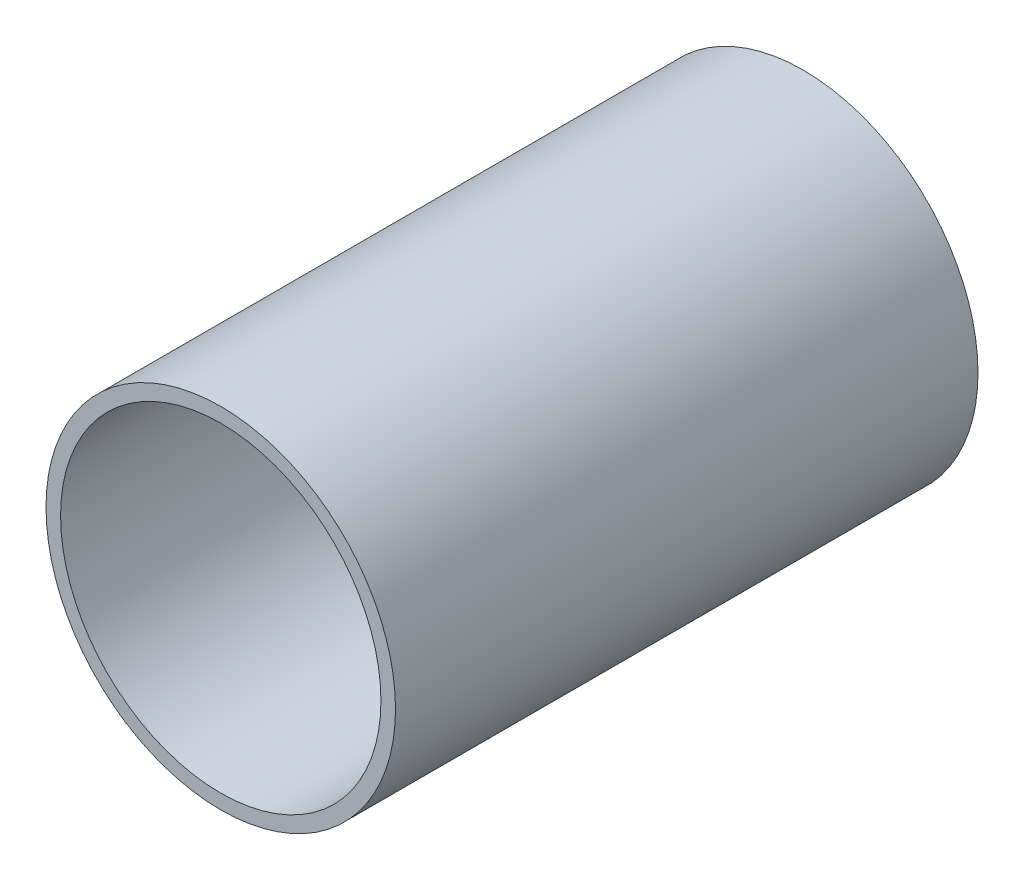
SolidWorks part; units mm, degrees
ref_plane "Plan de face" through (0, 0, 0) normal (0, 0, 1) x (1, 0, 0)
ref_plane "Plan de dessus" through (0, 0, 0) normal (0, 1, 0) x (1, 0, 0)
ref_plane "Plan de droite" through (0, 0, 0) normal (1, 0, 0) x (0, 0, -1)
sketch "Esquisse1" plane through (0, 0, 0) normal (0, 0, 1) x (1, 0, 0)
  circle A0 centre (0, 0) radius 24
extrude "Boss.-Extru.2" add sketch "Esquisse1" along normal blind 80
sketch "Esquisse2" plane through (0, 0, 80) normal (0, 0, 1) x (1, 0, 0)
  circle A0 centre (0, 0) radius 22
extrude "Enlèv. mat.-Extru.1" cut sketch "Esquisse2" against normal blind 80
